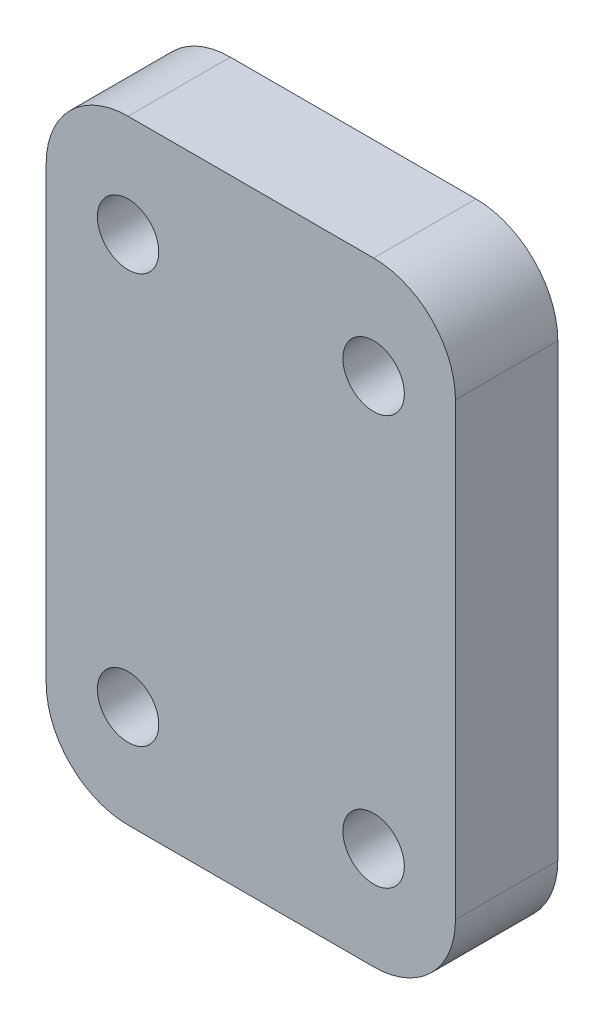
SolidWorks part; units mm, degrees
ref_plane "Front Plane" through (0, 0, 0) normal (0, 0, 1) x (1, 0, 0)
ref_plane "Top Plane" through (0, 0, 0) normal (0, 1, 0) x (1, 0, 0)
ref_plane "Right Plane" through (0, 0, 0) normal (1, 0, 0) x (0, 0, -1)
sketch "Sketch1" plane through (0, 0, 0) normal (0, 0, 1) x (1, 0, 0)
  line L0 (-20.5984, 10) -> (26.0825, 10) construction
  line L1 (-6, 15) -> (6, 15)
  line L2 (-10, 11) -> (-10, -11)
  line L3 (-6, -15) -> (6, -15)
  line L4 (10, 11) -> (10, -11)
  line L5 (-10, 15) -> (10, -15) construction
  line L6 (-10, -15) -> (10, 15) construction
  line L7 (-20.5984, -10) -> (26.0825, -10) construction
  line L8 (-6, 19.5876) -> (-6, -25.1546) construction
  line L9 (6, 19.5876) -> (6, -25.1546) construction
  circle A0 centre (-6, 10) radius 1.5
  circle A1 centre (6, 10) radius 1.5
  circle A2 centre (-6, -10) radius 1.5
  circle A3 centre (6, -10) radius 1.5
  arc A4 (6, -15) -> (10, -11) centre (6, -11) ccw
  arc A5 (-10, -11) -> (-6, -15) centre (-6, -11) ccw
  arc A6 (6, 15) -> (10, 11) centre (6, 11) cw
  arc A7 (-10, 11) -> (-6, 15) centre (-6, 11) cw
  point P0 (0, 0)
  dimension "D7" = 3
  dimension "D8" = 4
  dimension "D1" = 10
  dimension "D2" = 10
  dimension "D3" = 6
  dimension "D4" = 6
  dimension "D5" = 20
  dimension "D6" = 5
extrude "Boss-Extrude1" add sketch "Sketch1" along normal blind 5
